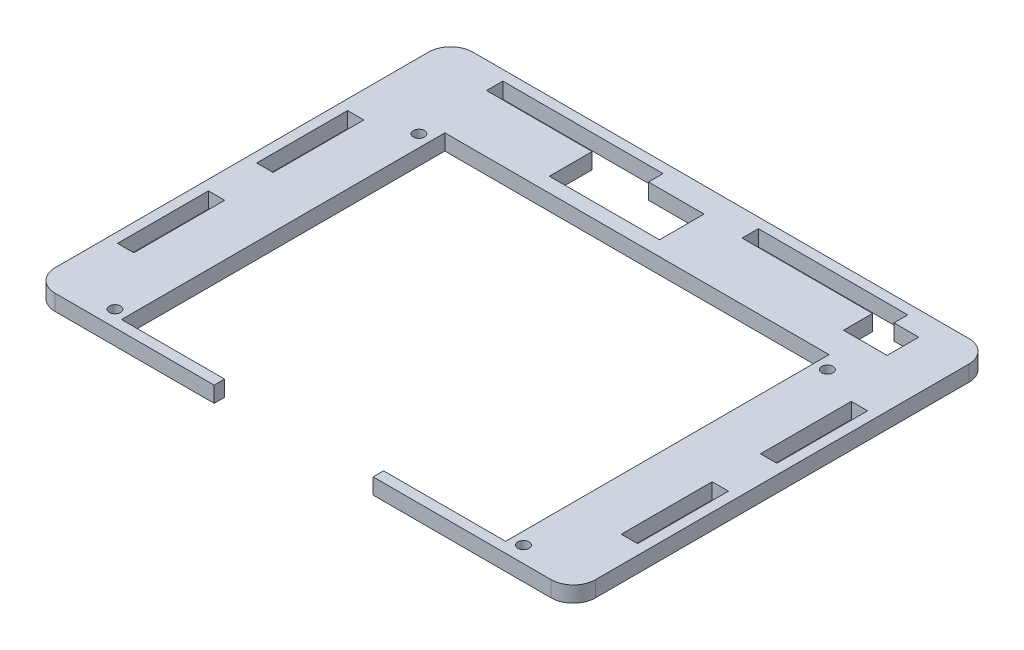
SolidWorks part; units mm, degrees
ref_plane "Front Plane" through (0, 0, 0) normal (0, 0, 1) x (1, 0, 0)
ref_plane "Top Plane" through (0, 0, 0) normal (0, 1, 0) x (1, 0, 0)
ref_plane "Right Plane" through (0, 0, 0) normal (1, 0, 0) x (0, 0, -1)
sketch "Sketch1" plane through (0, 0, 0) normal (0, 1, 0) x (1, 0, 0)
  line L0 (-38.5572, -41.9227) -> (-38.5572, 25.0825)
  line L1 (-54.229, 41.9227) -> (54.229, 41.9227)
  line L2 (-54.229, 41.9227) -> (-54.229, -41.9227)
  line L3 (-54.229, -41.9227) -> (-38.5572, -41.9227)
  line L4 (54.229, 41.9227) -> (54.229, -41.9227)
  line L5 (-38.5572, 25.0825) -> (38.5572, 25.0825)
  line L6 (38.5572, 25.0825) -> (38.5572, -41.9227)
  line L7 (38.5572, -41.9227) -> (54.229, -41.9227)
  line L8 (-51.943, 18.9357) -> (-51.943, 1.2065) construction
  line L9 (-51.943, -9.0043) -> (-49.1744, -9.0043) construction
  line L10 (-51.943, -9.0043) -> (-51.943, -26.7335) construction
  line L11 (-51.943, -26.7335) -> (-49.1744, -26.7335) construction
  line L12 (-49.1744, -9.0043) -> (-49.1744, -26.7335) construction
  line L13 (-49.1744, 18.9357) -> (-49.1744, 1.2065) construction
  line L14 (-51.943, 18.9357) -> (-49.1744, 18.9357) construction
  line L15 (-51.943, 1.2065) -> (-49.1744, 1.2065) construction
  line L16 (0, -1000) -> (0, 49000) construction
  line L17 (51.943, -26.7335) -> (49.1744, -26.7335) construction
  line L18 (49.1744, -9.0043) -> (49.1744, -26.7335) construction
  line L19 (51.943, -9.0043) -> (51.943, -26.7335) construction
  line L20 (51.943, -9.0043) -> (49.1744, -9.0043) construction
  line L21 (51.943, 1.2065) -> (49.1744, 1.2065) construction
  line L22 (51.943, 18.9357) -> (51.943, 1.2065) construction
  line L23 (51.943, 18.9357) -> (49.1744, 18.9357) construction
  line L24 (49.1744, 18.9357) -> (49.1744, 1.2065) construction
  line L25 (-20.2692, 36.8681) -> (-41.4782, 36.8681) construction
  line L26 (-41.4782, 36.8681) -> (-41.4782, 39.6367) construction
  line L27 (-9.8298, 39.6367) -> (-9.8298, 36.9697) construction
  line L28 (-9.8298, 36.9697) -> (1.3208, 36.9697) construction
  line L29 (1.3208, 36.9697) -> (1.3208, 28.2829) construction
  line L30 (1.3208, 28.2829) -> (-20.2692, 28.2829) construction
  line L31 (-20.2692, 28.2829) -> (-20.2692, 36.8681) construction
  line L32 (-41.4782, 39.6367) -> (-9.8298, 39.6367) construction
  line L33 (9.8298, 38.591) -> (9.8298, 39.6367) construction
  line L34 (9.8298, 39.6367) -> (39.2938, 39.6367) construction
  line L35 (39.2938, 39.6367) -> (39.2938, 36.8681) construction
  line L36 (39.2938, 36.8681) -> (44.2722, 36.8681) construction
  line L37 (44.2722, 36.8681) -> (44.2722, 31.0261) construction
  line L38 (44.2722, 31.0261) -> (36.0172, 31.0261) construction
  line L39 (36.0172, 31.0261) -> (36.0172, 36.8681) construction
  line L40 (36.0172, 36.8681) -> (9.8298, 36.8681) construction
  line L41 (9.8298, 36.8681) -> (9.8298, 38.591) construction
  line L42 (-52.197, 19.1897) -> (-52.197, 0.9525)
  line L43 (-52.197, 0.9525) -> (-48.9204, 0.9525)
  line L44 (-48.9204, 19.1897) -> (-48.9204, 0.9525)
  line L45 (-52.197, 19.1897) -> (-48.9204, 19.1897)
  line L46 (-52.197, -8.7503) -> (-48.9204, -8.7503)
  line L47 (-48.9204, -8.7503) -> (-48.9204, -26.9875)
  line L48 (-52.197, -26.9875) -> (-48.9204, -26.9875)
  line L49 (-52.197, -8.7503) -> (-52.197, -26.9875)
  line L50 (52.197, -26.9875) -> (48.9204, -26.9875)
  line L51 (48.9204, -8.7503) -> (48.9204, -26.9875)
  line L52 (52.197, -8.7503) -> (48.9204, -8.7503)
  line L53 (52.197, -8.7503) -> (52.197, -26.9875)
  line L54 (52.197, 0.9525) -> (48.9204, 0.9525)
  line L55 (48.9204, 19.1897) -> (48.9204, 0.9525)
  line L56 (52.197, 19.1897) -> (48.9204, 19.1897)
  line L57 (52.197, 19.1897) -> (52.197, 0.9525)
  line L58 (-20.5232, 36.6141) -> (-41.7322, 36.6141)
  line L59 (-41.7322, 36.6141) -> (-41.7322, 39.8907)
  line L60 (-41.7322, 39.8907) -> (-9.5758, 39.8907)
  line L61 (-9.5758, 39.8907) -> (-9.5758, 37.2237)
  line L63 (1.5748, 36.9697) -> (1.5748, 28.0289)
  line L64 (1.5748, 28.0289) -> (-20.5232, 28.0289)
  line L65 (-20.5232, 28.0289) -> (-20.5232, 36.6141)
  line L66 (9.5758, 38.591) -> (9.5758, 39.8907)
  line L67 (9.5758, 39.8907) -> (39.5478, 39.8907)
  line L68 (39.5478, 39.8907) -> (39.5478, 37.1221)
  line L69 (39.5478, 37.1221) -> (44.5262, 37.1221)
  line L70 (44.5262, 37.1221) -> (44.5262, 30.7721)
  line L71 (44.5262, 30.7721) -> (35.7632, 30.7721)
  line L72 (35.7632, 30.7721) -> (35.7632, 36.6141)
  line L73 (35.7632, 36.6141) -> (9.5758, 36.6141)
  line L74 (9.5758, 36.6141) -> (9.5758, 38.591)
  line L75 (-9.5758, 37.2237) -> (-9.5758, 36.9697)
  line L76 (-9.5758, 36.9697) -> (1.5748, 36.9697)
  line L77 (-9.5758, 37.2237) -> (1.5748, 37.2237) construction
  line L78 (1.5748, 37.2237) -> (1.5748, 28.0289) construction
  circle A0 centre (-40.9956, -38.6969) radius 1.1303
  circle A1 centre (-40.9956, 22.3139) radius 1.1303
  circle A2 centre (40.9956, 22.3139) radius 1.1303
  circle A3 centre (40.9956, -38.6969) radius 1.1303
  dimension "D8" = 2.2606
  dimension "D9" = 2.2606
  dimension "D10" = 2.2606
  dimension "D11" = 2.2606
  dimension "D1" = 83.8454
  dimension "D2" = 108.458
  dimension "D3" = 54.229
  dimension "D4" = 41.9227
  dimension "D5" = 15.6718
  dimension "D6" = 15.6718
  dimension "D7" = 67.0052
  dimension "D12" = 2.4384
  dimension "D13" = 3.2258
  dimension "D14" = 2.4384
  dimension "D15" = 3.2258
  dimension "D16" = 19.6088
  dimension "D17" = 2.4384
  dimension "D18" = 19.6088
  dimension "D19" = 2.4384
  dimension "D20" = 17.7292
  dimension "D21" = 2.7686
  dimension "D22" = 15.1892
  dimension "D23" = 2.286
  dimension "D25" = 2.667
  dimension "D26" = 11.1506
  dimension "D27" = 8.6868
  dimension "D28" = 21.59
  dimension "D29" = 8.5852
  dimension "D30" = 21.209
  dimension "D31" = 33.9598
  dimension "D32" = 2.286
  dimension "D33" = 26.1874
  dimension "D34" = 2.7686
  dimension "D35" = 4.9784
  dimension "D36" = 5.842
  dimension "D37" = 8.255
  dimension "D38" = 5.842
  dimension "D39" = 9.9568
  dimension "D40" = 2.286
  dimension "D41" = 0.254
  dimension "D42" = 0.254
  dimension "D24" = 2
extrude "Boss-Extrude1" add sketch "Sketch1" along normal mid plane 3.175
fillet "Fillet1" radius 4.445 4 edges at (54.229, 0, 41.9227) (54.229, 0, -41.9227) (-54.229, 0, -41.9227) (-54.229, 0, 41.9227)
sketch "Sketch2" plane through (0, 1.5875, 0) normal (0, 1, 0) x (1, 0, 0)
  line L0 (-40.9956, -39.8272) -> (40.9956, -39.8272)
  line L1 (40.9956, -39.8272) -> (40.9956, -41.9227)
  line L2 (38.5572, -41.9227) -> (49.784, -41.9227) construction
  line L3 (40.9956, -41.9227) -> (-40.9956, -41.9227)
  line L4 (-49.784, -41.9227) -> (-38.5572, -41.9227) construction
  line L5 (-40.9956, -41.9227) -> (-40.9956, -39.8272)
  circle A0 centre (-40.9956, -38.6969) radius 1.1303 construction
  circle A1 centre (40.9956, -38.6969) radius 1.1303 construction
extrude "Boss-Extrude2" add sketch "Sketch2" against normal blind 3.175
sketch "Sketch3" plane through (0, 1.5875, 0) normal (0, 1, 0) x (1, 0, 0)
  line L0 (38.5572, -39.8272) -> (-38.5572, -39.8272) construction
  line L1 (-17.8562, -39.8272) -> (14.0462, -39.8272)
  line L2 (-17.8562, -39.8272) -> (-17.8562, -41.9227)
  line L3 (-17.8562, -41.9227) -> (14.0462, -41.9227)
  line L4 (14.0462, -39.8272) -> (14.0462, -41.9227)
  line L5 (-49.784, -41.9227) -> (49.784, -41.9227) construction
  line L6 (-38.5572, -39.8272) -> (-38.5572, 25.0825) construction
  line L7 (38.5572, 25.0825) -> (38.5572, -39.8272) construction
  dimension "D1" = 20.701
  dimension "D2" = 24.511
extrude "Cut-Extrude1" cut sketch "Sketch3" against normal blind 3.175
equation "\"D3@Sketch1\"=.5*\"D2@Sketch1\""
equation "\"D4@Sketch1\"=.5*\"D1@Sketch1\""
